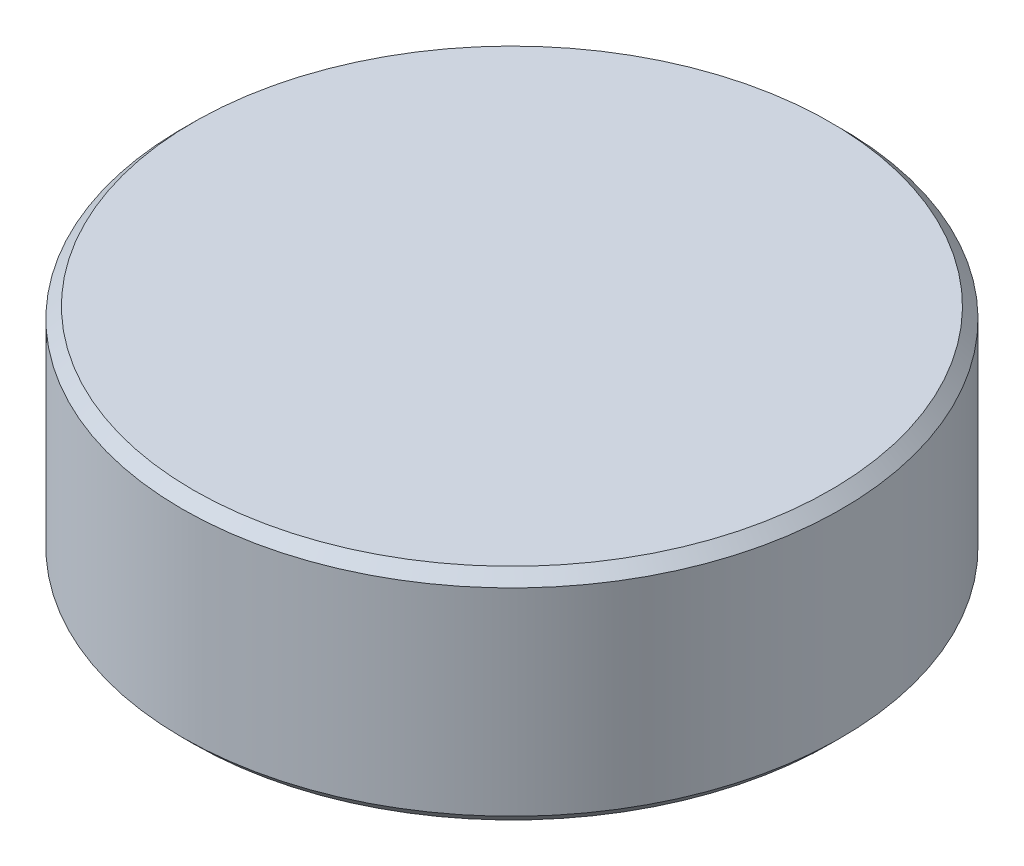
SolidWorks part; units mm, degrees
ref_plane "Front Plane" through (0, 0, 0) normal (0, 0, 1) x (1, 0, 0)
ref_plane "Top Plane" through (0, 0, 0) normal (0, 1, 0) x (1, 0, 0)
ref_plane "Right Plane" through (0, 0, 0) normal (1, 0, 0) x (0, 0, -1)
sketch "Sketch1" plane through (0, 0, 0) normal (0, 1, 0) x (1, 0, 0)
  circle A0 centre (0, 0) radius 3
  dimension "D1" = 6
extrude "Boss-Extrude1" add sketch "Sketch1" along normal blind 2
chamfer "Chamfer1" distance 0.1 angle 45 2 edges at (0, 0, 3) (0, 2, 3)
